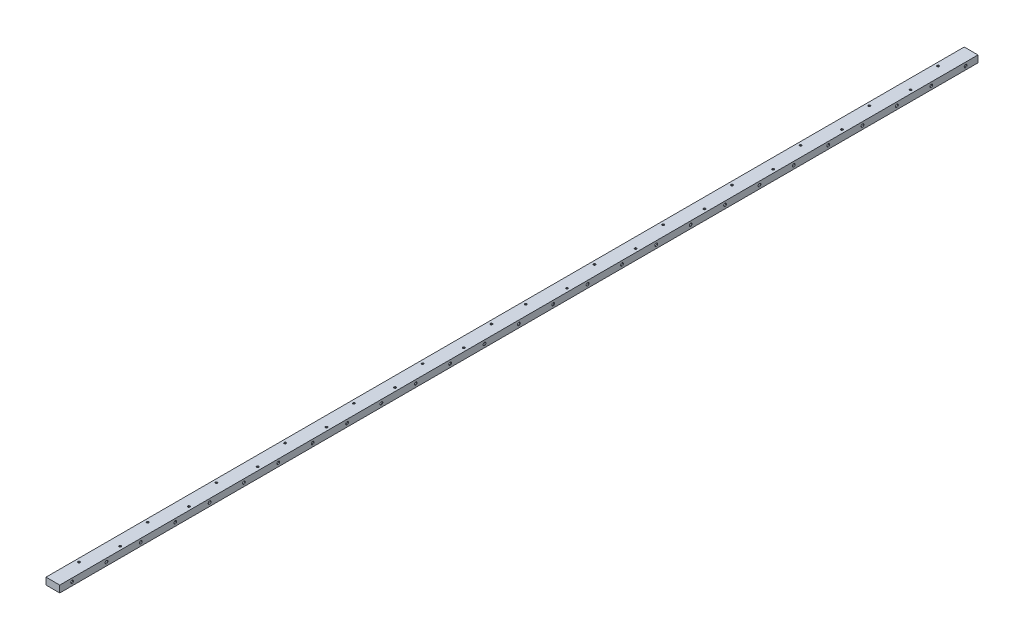
SolidWorks part; units mm, degrees
material "Plain Carbon Steel"
ref_plane "Front Plane" through (0, 0, 0) normal (0, 0, 1) x (1, 0, 0)
ref_plane "Top Plane" through (0, 0, 0) normal (0, 1, 0) x (1, 0, 0)
ref_plane "Right Plane" through (0, 0, 0) normal (1, 0, 0) x (0, 0, -1)
sketch "Sketch1" plane through (0, 0, 0) normal (0, 0, 1) x (1, 0, 0)
  line L1 (-10, -5) -> (10, -5)
  line L2 (-10, -5) -> (-10, 5)
  line L3 (-10, 5) -> (10, 5)
  line L4 (10, -5) -> (10, 5)
  line L5 (-10, -5) -> (10, 5) construction
  line L6 (-10, 5) -> (10, -5) construction
  point P0 (0, 0)
  dimension "D1" = 10
  dimension "D2" = 20
extrude "Boss-Extrude1" add sketch "Sketch1" along normal mid plane 1336
sketch "Sketch4" plane through (0, 5, 0) normal (0, 1, 0) x (1, 0, 0)
  line L0 (0, 0) -> (-5, 0) construction
  line L1 (-5, 0) -> (-5, 75) construction
  line L2 (-5, 75) -> (5, 75) construction
  line L3 (5, 75) -> (5, 0) construction
  line L4 (5, 0) -> (0, 0) construction
  line L5 (5, 37.5) -> (-5, 37.5) construction
  circle A0 centre (-5, 25) radius 1.25
  circle A1 centre (5, 75) radius 1.25
  dimension "D3" = 2.5
  dimension "D4" = 25
  dimension "D1" = 75
  dimension "D2" = 10
hole_wizard "M3x0.5 Tapped Hole1" positions "Sketch5" profile "Sketch6" tap size "M3x0.5" standard "ANSI Metric"
sketch "Sketch5" plane through (0, 5, 0) normal (0, 1, 0) x (1, 0, 0)
  point P0 (-5, 25)
  point P3 (5, 75)
sketch "Sketch6" plane through (-5, 5, -25) normal (1, 0, 0) x (0, 0, 1)
  line L0 (0, 0) -> (0, 8.7511)
  line L1 (0, 8.7511) -> (1.25, 8)
  line L2 (1.25, 8) -> (1.25, 0.7243)
  line L3 (1.25, 0.7243) -> (1.55, 0)
  line L5 (1.55, 0) -> (0, 0)
  line L6 (-1.25, 0.7243) -> (-1.55, 0) construction
  line L10 (0, 8.7511) -> (-1.25, 8) construction
  line L11 (0, -6.35) -> (0, 107.95) construction
  dimension "Tap Drill Dia." = 2.5
  dimension "Tap Drill Depth" = 8
  dimension "Near C'Sink Dia." = 3.1
  dimension "Near C'Sink Angle" = 45
  dimension "Drill Angle" = 118
cosmetic thread "Hole Thread1" parameters "D1"=6, "D2"=3
cosmetic thread "Hole Thread2" parameters "D1"=6, "D2"=3
pattern_linear "LPattern1" count 13 spacing 100 along (0, 0, -1) of "M3x0.5 Tapped Hole1"
hole_wizard "M4x0.7 Tapped Hole1" positions "Sketch7" profile "Sketch8" tap size "M4x0.7" standard "ANSI Metric" end condition through all
sketch "Sketch7" plane through (10, 0, 0) normal (1, 0, 0) x (0, 0, -1)
  point P0 (0, 0)
sketch "Sketch8" plane through (10, 0, 0) normal (0, 1, 0) x (0, 0, -1)
  line L0 (0, 0) -> (0, 20)
  line L1 (0, 20) -> (2.05, 20)
  line L2 (1.65, 19.6) -> (1.65, 0.9657)
  line L3 (1.65, 0.9657) -> (2.05, 0)
  line L5 (2.05, 0) -> (0, 0)
  line L6 (-1.65, 0.9657) -> (-2.05, 0) construction
  line L7 (2.05, 20) -> (1.65, 19.6)
  line L8 (-2.05, 20) -> (-1.65, 19.6) construction
  line L11 (0, -6.35) -> (0, 107.95) construction
  dimension "Thru Tap Drill Dia." = 3.3
  dimension "Thru Tap Drill Depth" = 20
  dimension "Near C'Sink Dia." = 4.1
  dimension "Near C'Sink Angle" = 45
  dimension "Far C'Sink Dia." = 4.1
  dimension "Far C'Sink Angle" = 90
cosmetic thread "Hole Thread3" parameters "D2"=4
pattern_linear "LPattern2" count 14 spacing 50 along (0, 0, 1) count 14 spacing 50 along (0, 0, -1) of "M4x0.7 Tapped Hole1"
mirror "Mirror1" about plane through (0, 0, 0) normal (0, 0, 1) of "LPattern1", "M3x0.5 Tapped Hole1"
